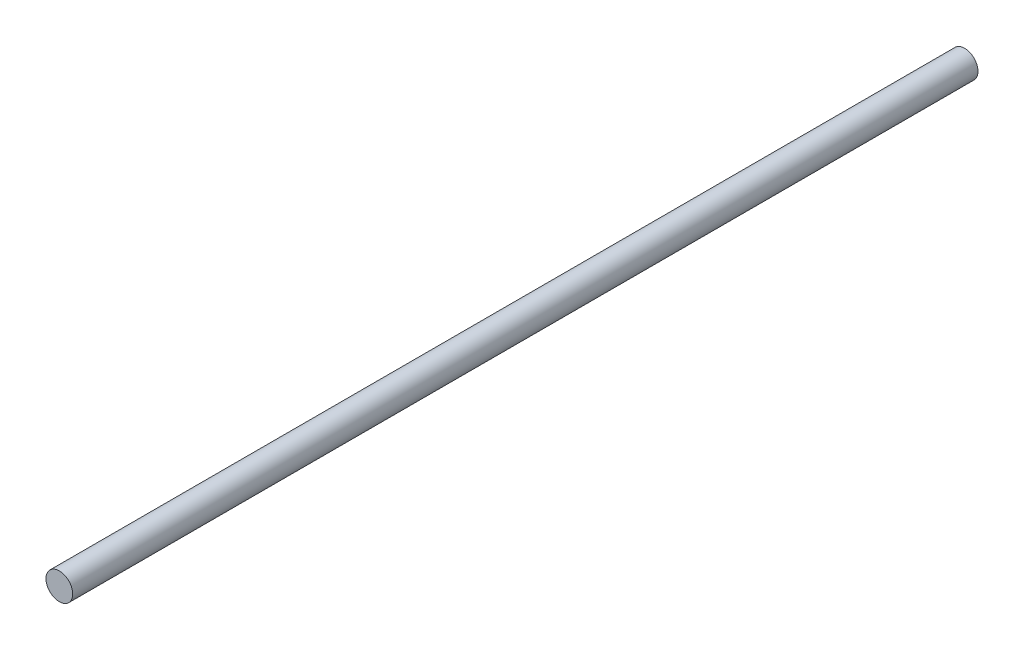
SolidWorks part; units mm, degrees
material "Plain Carbon Steel"
ref_plane "Front Plane" through (0, 0, 0) normal (0, 0, 1) x (1, 0, 0)
ref_plane "Top Plane" through (0, 0, 0) normal (0, 1, 0) x (1, 0, 0)
ref_plane "Right Plane" through (0, 0, 0) normal (1, 0, 0) x (0, 0, -1)
sketch "Sketch1" plane through (0, 0, 0) normal (0, 0, 1) x (1, 0, 0)
  circle A0 centre (0, 0) radius 1.55
  dimension "D1" = 3.1
extrude "Boss-Extrude1" add sketch "Sketch1" along normal blind 105
